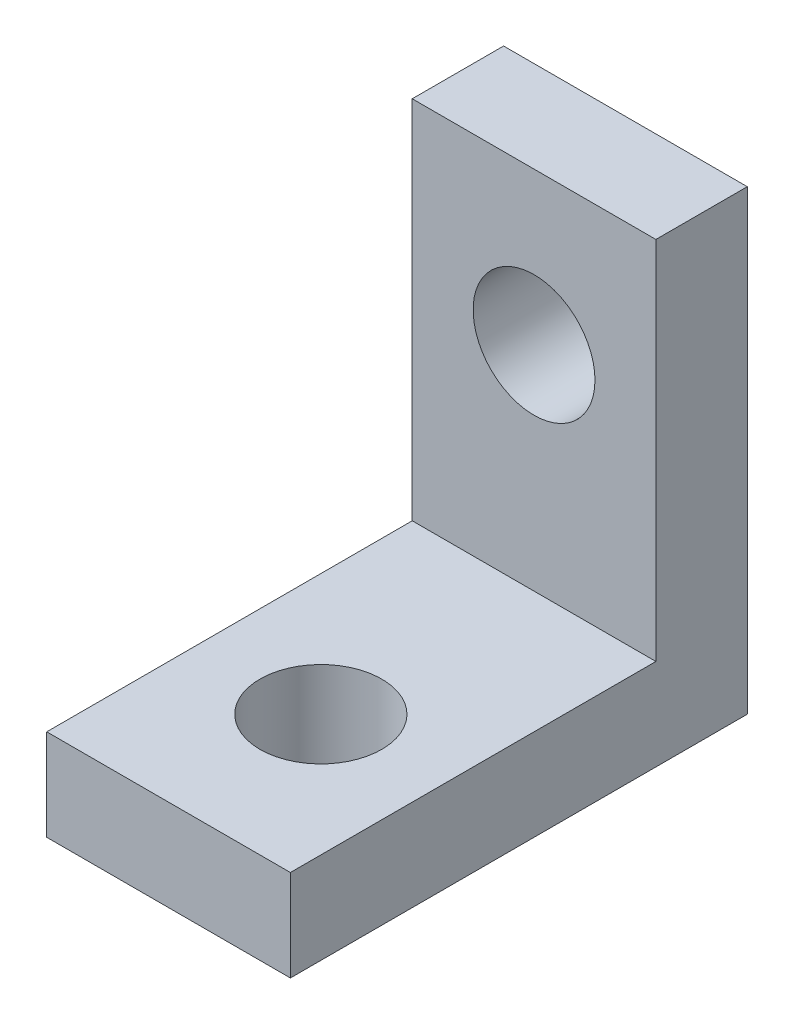
SolidWorks part; units mm, degrees
ref_plane "Plan de face" through (0, 0, 0) normal (0, 0, 1) x (1, 0, 0)
ref_plane "Plan de dessus" through (0, 0, 0) normal (0, 1, 0) x (1, 0, 0)
ref_plane "Plan de droite" through (0, 0, 0) normal (1, 0, 0) x (0, 0, -1)
sketch "Esquisse1" plane through (0, 0, 0) normal (0, 0, 1) x (1, 0, 0)
  line L1 (-4, 1.5) -> (4, 1.5)
  line L2 (-4, 1.5) -> (-4, -1.5)
  line L3 (-4, -1.5) -> (4, -1.5)
  line L4 (4, 1.5) -> (4, -1.5)
  line L5 (-4, 1.5) -> (4, -1.5) construction
  line L6 (-4, -1.5) -> (4, 1.5) construction
  point P0 (0, 0)
  dimension "D1" = 3
  dimension "D2" = 8
extrude "Boss.-Extru.1" add sketch "Esquisse1" along normal blind 15
sketch "Esquisse2" plane through (0, 1.5, 0) normal (0, 1, 0) x (1, 0, 0)
  line L0 (4, -15) -> (4, 0) construction
  line L1 (-4, 0) -> (4, 0)
  line L2 (-4, 0) -> (-4, -3)
  line L3 (-4, -3) -> (4, -3)
  line L4 (4, 0) -> (4, -3)
  dimension "D1" = 3
extrude "Boss.-Extru.2" add sketch "Esquisse2" along normal blind 12
sketch "Esquisse3" plane through (0, 1.5, 0) normal (0, 1, 0) x (1, 0, 0)
  line L0 (4, -15) -> (-4, -15) construction
  circle A0 centre (0, -10) radius 2
  dimension "D1" = 4
  dimension "D2" = 5
extrude "Enlèv. mat.-Extru.1" cut sketch "Esquisse3" against normal through all
sketch "Esquisse4" plane through (0, 0, 3) normal (0, 0, 1) x (1, 0, 0)
  line L0 (-4, 13.5) -> (4, 13.5) construction
  circle A0 centre (0, 8.5) radius 2
  dimension "D1" = 4
  dimension "D2" = 5
extrude "Enlèv. mat.-Extru.2" cut sketch "Esquisse4" against normal through all
